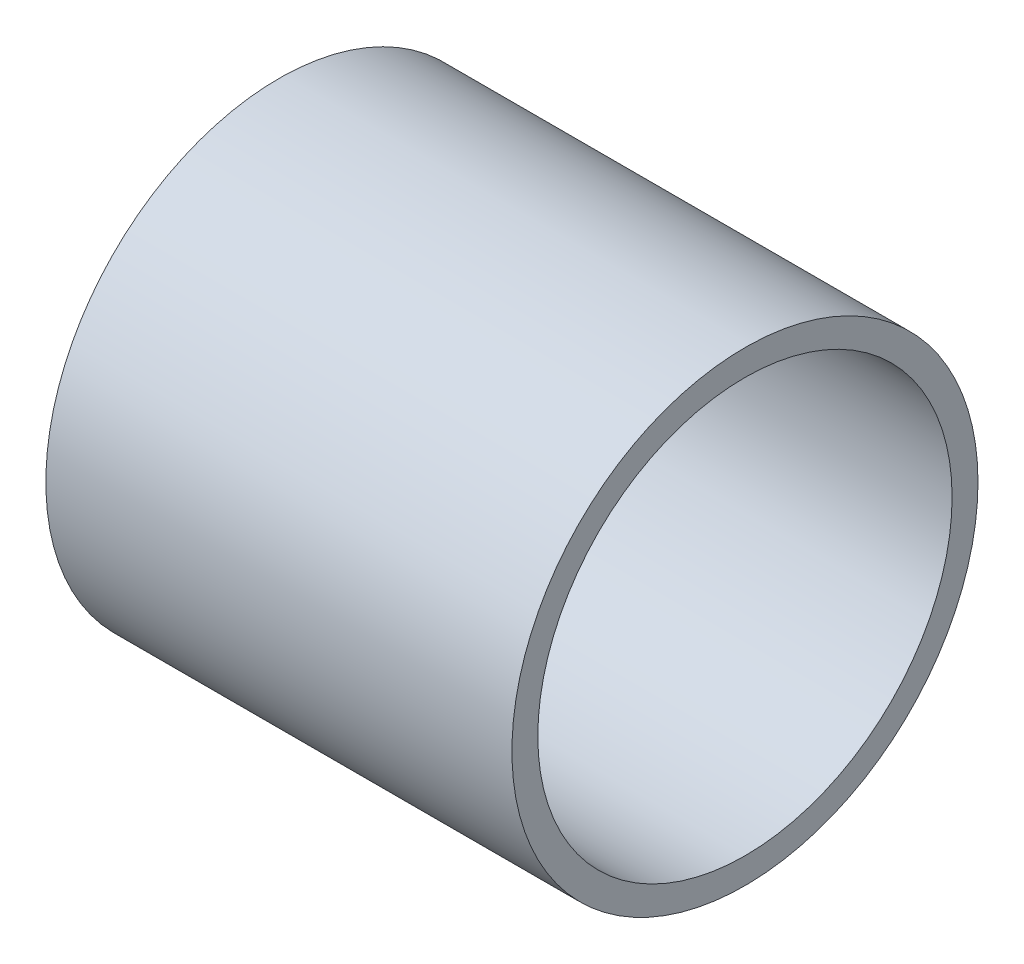
SolidWorks part; units mm, degrees
ref_plane "Front Plane" through (0, 0, 0) normal (0, 0, 1) x (1, 0, 0)
ref_plane "Top Plane" through (0, 0, 0) normal (0, 1, 0) x (1, 0, 0)
ref_plane "Right Plane" through (0, 0, 0) normal (1, 0, 0) x (0, 0, -1)
sketch "Sketch1" plane through (0, 0, 0) normal (1, 0, 0) x (0, 0, -1)
  circle A0 centre (0, 0) radius 4.5
extrude "Boss-Extrude1" add sketch "Sketch1" along normal blind 9 contours A0
sketch "Sketch2" plane through (0, 0, 0) normal (-1, 0, 0) x (0, 0, 1)
  circle A0 centre (0, 0) radius 4
extrude "Cut-Extrude1" cut sketch "Sketch2" along normal blind 2 and the other way blind 12 contours A0
